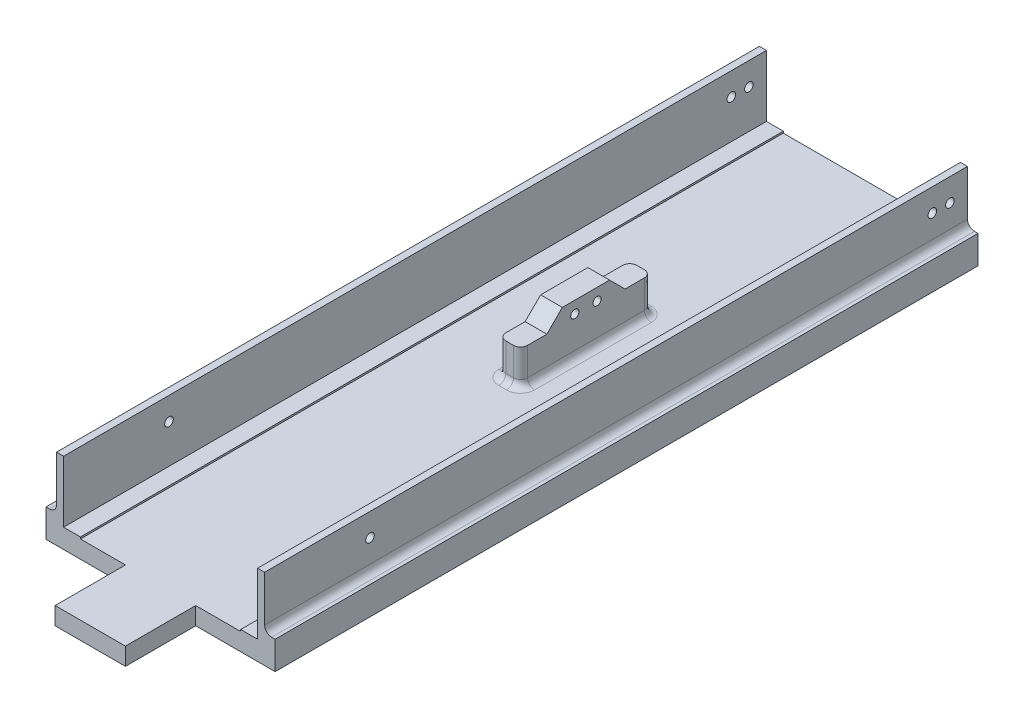
SolidWorks part; units mm, degrees
ref_plane "Front Plane" through (0, 0, 0) normal (0, 0, 1) x (1, 0, 0)
ref_plane "Top Plane" through (0, 0, 0) normal (0, 1, 0) x (1, 0, 0)
ref_plane "Right Plane" through (0, 0, 0) normal (1, 0, 0) x (0, 0, -1)
sketch "Sketch1" plane through (0, 0, 0) normal (0, 0, 1) x (1, 0, 0)
  line L0 (0, 0) -> (0, 25)
  line L1 (0, 25) -> (5, 25)
  line L2 (5, 25) -> (5, 5)
  line L3 (5, 5) -> (60.2, 5)
  line L4 (60.2, 5) -> (60.2, 25)
  line L5 (60.2, 25) -> (65.2, 25)
  line L6 (65.2, 25) -> (65.2, 0)
  line L7 (65.2, 0) -> (0, 0)
  dimension "D1" = 5
  dimension "D2" = 5
  dimension "D3" = 55.2
  dimension "D4" = 5
  dimension "D5" = 20
  dimension "D6" = 20
extrude "Boss-Extrude1" add sketch "Sketch1" along normal blind 400
sketch "Sketch2" plane through (0, 5, 0) normal (0, 1, 0) x (1, 0, 0)
  line L1 (29.51, -63.42) -> (35.69, -63.42)
  line L2 (29.51, -63.42) -> (29.51, -100.67)
  line L3 (29.51, -100.67) -> (35.69, -100.67)
  line L4 (35.69, -63.42) -> (35.69, -100.67)
  line L7 (60.2, -400) -> (5, -400) construction
  line L10 (0, -400) -> (0, 0) construction
  circle A0 centre (32.6, -67.17) radius 2.1
  circle A1 centre (32.6, -96.92) radius 2.1
  circle A2 centre (32.6, -67.17) radius 2.1
  circle A3 centre (32.6, -96.92) radius 2.1
  dimension "D5" = 4.2
  dimension "D1" = 6.18
  dimension "D2" = 37.25
  dimension "D3" = 299.33
  dimension "D4" = 29.51
  dimension "D6" = 3.75
  dimension "D7" = 33.5
  dimension "D8" = 3.09
  dimension "D9" = 3.09
extrude "Cut-Extrude3" cut sketch "Sketch2" against normal blind 10 contours A0 | A1
sketch "Sketch3" plane through (0, 25, 0) normal (0, 1, 0) x (1, 0, 0)
  line L1 (-34.8959, 47.3477) -> (123.1433, 47.3477)
  line L2 (-34.8959, 47.3477) -> (-34.8959, -450.6402)
  line L3 (-34.8959, -450.6402) -> (123.1433, -450.6402)
  line L4 (123.1433, 47.3477) -> (123.1433, -450.6402)
extrude "Cut-Extrude4" cut sketch "Sketch3" against normal blind 2
sketch "Sketch4" plane through (0, 5, 0) normal (0, 1, 0) x (1, 0, 0)
  line L0 (60.2, -400) -> (5, -400) construction
  line L1 (5, 0) -> (9.8, 0)
  line L2 (5, 0) -> (5, -400)
  line L3 (5, -400) -> (9.8, -400)
  line L4 (9.8, 0) -> (9.8, -400)
  line L5 (60.2, 0) -> (5, 0) construction
  line L6 (55.4, 0) -> (60.2, 0)
  line L7 (55.4, 0) -> (55.4, -400)
  line L8 (55.4, -400) -> (60.2, -400)
  line L9 (60.2, 0) -> (60.2, -400)
  dimension "D1" = 4.8
  dimension "D2" = 4.8
extrude "Boss-Extrude2" add sketch "Sketch4" along normal blind 8
sketch "Sketch5" plane through (5, 0, 0) normal (1, 0, 0) x (0, 0, -1)
  line L0 (-400, 13) -> (-400, 23) construction
  line L1 (0, 13) -> (-400, 13) construction
  line L2 (-200, 13) -> (-200, 23)
  line L3 (-400, 23) -> (0, 23) construction
  line L4 (-400, 0) -> (-400, 23) construction
  circle A0 centre (-395, 16.5) radius 1.2
  circle A1 centre (-390, 16.5) radius 1.2
  circle A2 centre (-5, 16.5) radius 1.2
  circle A3 centre (-10, 16.5) radius 1.2
  dimension "D1" = 2.4
  dimension "D2" = 2.4
  dimension "D3" = 5
  dimension "D4" = 10
  dimension "D5" = 3.5
  dimension "D6" = 3.5
  dimension "D7" = 200
extrude "Cut-Extrude9" cut sketch "Sketch5" against normal through all contours A0 | A1 | A3 | A2
sketch "Sketch9" plane through (0, 0, 0) normal (-1, 0, 0) x (0, 0, 1)
  circle A0 centre (5, 16.5) radius 1.225
  circle A1 centre (10, 16.5) radius 1.225
  circle A2 centre (390, 16.5) radius 1.225
  circle A3 centre (395, 16.5) radius 1.225
  dimension "D1" = 2.45
extrude "Cut-Extrude10" cut sketch "Sketch9" against normal through all
sketch "Sketch10" plane through (0, 13, 0) normal (0, 1, 0) x (1, 0, 0)
  line L1 (5, 0) -> (9.8, 0)
  line L2 (5, 0) -> (5, -400)
  line L3 (5, -400) -> (9.8, -400)
  line L4 (9.8, 0) -> (9.8, -400)
  line L5 (55.4, -400) -> (60.2, -400)
  line L6 (55.4, -400) -> (55.4, 0)
  line L7 (55.4, 0) -> (60.2, 0)
  line L8 (60.2, -400) -> (60.2, 0)
extrude "Cut-Extrude11" cut sketch "Sketch10" against normal blind 5
sketch "Sketch12" plane through (0, 0, 0) normal (0, -1, 0) x (1, 0, 0)
  circle A0 centre (32.6, 96.92) radius 2.1
  circle A1 centre (32.6, 67.17) radius 2.1
extrude "Boss-Extrude3" add sketch "Sketch12" against normal blind 15
sketch "Sketch13" plane through (0, 5, 0) normal (0, 1, 0) x (1, 0, 0)
  line L1 (29.51, -63.42) -> (35.69, -63.42)
  line L2 (29.51, -63.42) -> (29.51, -100.67)
  line L3 (29.51, -100.67) -> (35.69, -100.67)
  line L4 (35.69, -63.42) -> (35.69, -100.67)
  circle A0 centre (32.6, -67.17) radius 2.1 construction
  circle A1 centre (32.6, -67.17) radius 2.1 construction
  dimension "D2" = 3.75
  dimension "D1" = 3.09
  dimension "D3" = 37.25
  dimension "D4" = 6.18
extrude "Boss-Extrude5" add sketch "Sketch13" along normal blind 10
sketch "Sketch14" plane through (29.51, 0, 0) normal (-1, 0, 0) x (0, 0, 1)
  line L0 (70.92, 15) -> (75.32, 19.4)
  line L1 (63.42, 15) -> (100.67, 15) construction
  line L2 (75.32, 19.4) -> (88.77, 19.4)
  line L3 (88.77, 19.4) -> (93.17, 15)
  line L4 (63.42, 15) -> (63.42, 5) construction
  line L5 (70.92, 15) -> (93.17, 15)
  dimension "D1" = 13.45
  dimension "D2" = 4.4
  dimension "D3" = 4.4
  dimension "D4" = 4.4
  dimension "D5" = 7.5
extrude "Boss-Extrude6" add sketch "Sketch14" against normal up to surface (6.18 mm away) up to face at (35.69, 10, 82.045)
sketch "Sketch15" plane through (29.51, 0, 0) normal (-1, 0, 0) x (0, 0, 1)
  line L0 (100.67, 15) -> (100.67, 5) construction
  line L1 (63.42, 15) -> (63.42, 5) construction
  line L2 (88.77, 19.4) -> (75.32, 19.4) construction
  circle A0 centre (78.87, 16) radius 1.05
  circle A1 centre (85.22, 16) radius 1.05
  dimension "D4" = 3.4
  dimension "D5" = 2.1
  dimension "D6" = 2.1
  dimension "D1" = 15.45
  dimension "D2" = 15.45
  dimension "D3" = 3.4
extrude "Cut-Extrude12" cut sketch "Sketch15" against normal blind 10
fillet "Fillet1" radius 2 8 edges at (29.51, 10, 100.67) (35.69, 10, 100.67) (35.69, 10, 63.42) (29.51, 10, 63.42) (32.6, 5, 100.67) (35.69, 5, 82.045) (32.6, 5, 63.42) (29.51, 5, 82.045)
sketch "Sketch16" plane through (0, 8, 0) normal (0, 1, 0) x (1, 0, 0)
  line L1 (5, 0) -> (9.8, 0)
  line L2 (5, 0) -> (5, -400)
  line L3 (5, -400) -> (9.8, -400)
  line L4 (9.8, 0) -> (9.8, -400)
  line L5 (55.4, -400) -> (60.2, -400)
  line L6 (55.4, -400) -> (55.4, 0)
  line L7 (55.4, 0) -> (60.2, 0)
  line L8 (60.2, -400) -> (60.2, 0)
extrude "Cut-Extrude13" cut sketch "Sketch16" against normal blind 2.5
sketch "Sketch17" plane through (29.51, 0, 0) normal (-1, 0, 0) x (0, 0, 1)
  circle A0 centre (78.87, 16) radius 1.16
  circle A1 centre (85.22, 16) radius 1.16
  dimension "D1" = 2.32
  dimension "D2" = 2.32
extrude "Cut-Extrude14" cut sketch "Sketch17" against normal up to next
sketch "Sketch18" plane through (60.2, 0, 0) normal (-1, 0, 0) x (0, 0, 1)
  line L0 (5, 16.5) -> (170, 16.5)
  circle A0 centre (170, 16.5) radius 1.225
  circle A1 centre (5, 16.5) radius 1.225 construction
  dimension "D1" = 165
extrude "Cut-Extrude16" cut sketch "Sketch18" against normal through all and the other way through all
sketch "Sketch20" plane through (60.2, 0, 0) normal (-1, 0, 0) x (0, 0, 1)
  line L0 (395, 16.5) -> (230, 16.5)
  circle A0 centre (230, 16.5) radius 1.225
  circle A1 centre (395, 16.5) radius 1.225 construction
  dimension "D1" = 165
extrude "Cut-Extrude17" cut sketch "Sketch20" against normal through all and the other way through all
sketch "Sketch22" plane through (0, 0, 0) normal (0, 0, -1) x (-1, 0, 0)
  line L1 (-65.2, 23) -> (-62.2, 23)
  line L2 (-65.2, 23) -> (-65.2, 8)
  line L3 (-65.2, 8) -> (-62.2, 8)
  line L4 (-62.2, 23) -> (-62.2, 8)
  line L5 (0, 23) -> (-3, 23)
  line L6 (0, 23) -> (0, 8)
  line L7 (0, 8) -> (-3, 8)
  line L8 (-3, 23) -> (-3, 8)
  dimension "D1" = 15
  dimension "D2" = 3
  dimension "D3" = 3
  dimension "D4" = 15
extrude "Cut-Extrude18" cut sketch "Sketch22" against normal through all
fillet "Fillet2" radius 2 1 edges at (62.2, 8, 200)
fillet "Fillet3" radius 2 1 edges at (3, 8, 200)
sketch "Sketch24" plane through (0, 23, 0) normal (0, 1, 0) x (1, 0, 0)
  line L0 (0, -200) -> (65.2, -200)
  line L1 (0, 0) -> (65.2, 0)
  line L2 (0, 0) -> (0, -400)
  line L3 (0, -400) -> (65.2, -400)
  line L4 (65.2, 0) -> (65.2, -400)
  line L6 (22.6, -200) -> (42.6, -200)
  line L7 (22.6, -200) -> (22.6, -220)
  line L8 (22.6, -220) -> (42.6, -220)
  line L9 (42.6, -200) -> (42.6, -220)
  line M3 (62.2, -400) -> (62.2, 0)
  line M5 (60.2, 0) -> (60.2, -400)
  line M6 (60.2, -400) -> (62.2, -400)
  dimension "D1" = 20
  dimension "D2" = 22.6
  dimension "D3" = 20
extrude "Cut-Extrude20" cut sketch "Sketch24" against normal through all contours L0 L9 L8 L7 L2 L3 M5 | L4 L0 L3 M3 | L0 M5 M6 M3
